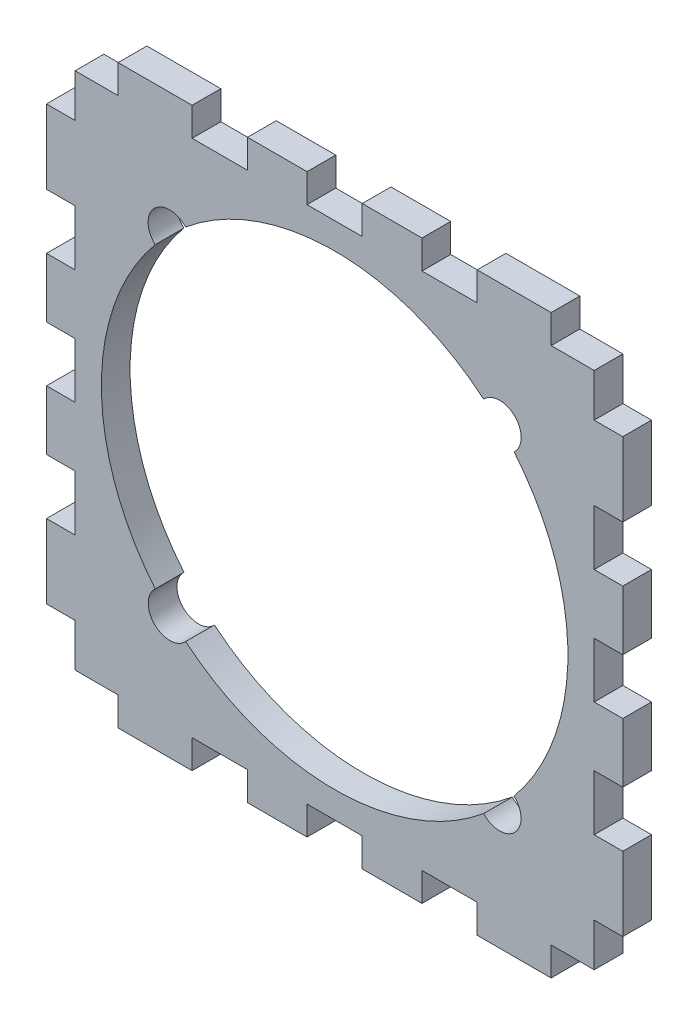
SolidWorks part; units mm, degrees
ref_plane "Front Plane" through (0, 0, 0) normal (0, 0, 1) x (1, 0, 0)
ref_plane "Top Plane" through (0, 0, 0) normal (0, 1, 0) x (1, 0, 0)
ref_plane "Right Plane" through (0, 0, 0) normal (1, 0, 0) x (0, 0, -1)
sketch "Model" plane through (0, 0, 0) normal (0, 0, 1) x (1, 0, 0)
  line L0 (-5.9972, 216.8283) -> (0, 216.8283)
  line L1 (0, 216.8283) -> (0, 220.8147)
  line L2 (0, 220.8147) -> (10.3011, 220.8147)
  line L3 (10.3011, 220.8147) -> (10.3011, 216.8283)
  line L4 (10.3011, 216.8283) -> (18.0269, 216.8283)
  line L5 (18.0269, 216.8283) -> (18.0269, 220.8147)
  line L6 (18.0269, 220.8147) -> (26.3172, 220.8147)
  line L7 (26.3172, 220.8147) -> (26.3172, 216.8283)
  line L8 (26.3172, 216.8283) -> (34.0078, 216.8283)
  line L9 (34.0078, 216.8283) -> (34.0078, 220.8147)
  line L10 (34.0078, 220.8147) -> (42.3333, 220.8147)
  line L11 (42.3333, 220.8147) -> (42.3333, 216.8283)
  line L12 (42.3333, 216.8283) -> (50.0239, 216.8283)
  line L13 (50.0239, 216.8283) -> (50.0239, 220.8147)
  line L14 (50.0239, 220.8147) -> (60.325, 220.8147)
  line L15 (60.325, 220.8147) -> (60.325, 216.8283)
  line L16 (60.325, 216.8283) -> (66.3222, 216.8283)
  line L17 (66.3222, 216.8283) -> (66.3222, 210.8311)
  line L18 (66.3222, 210.8311) -> (70.3086, 210.8311)
  line L19 (70.3086, 210.8311) -> (70.3086, 200.53)
  line L20 (70.3086, 200.53) -> (66.3222, 200.53)
  line L21 (66.3222, 200.53) -> (66.3222, 192.8042)
  line L22 (66.3222, 192.8042) -> (70.3086, 192.8042)
  line L23 (70.3086, 192.8042) -> (70.3086, 184.5139)
  line L24 (70.3086, 184.5139) -> (66.3222, 184.5139)
  line L25 (66.3222, 184.5139) -> (66.3222, 176.8233)
  line L26 (66.3222, 176.8233) -> (70.3086, 176.8233)
  line L27 (70.3086, 176.8233) -> (70.3086, 168.533)
  line L28 (70.3086, 168.533) -> (66.3222, 168.533)
  line L29 (66.3222, 168.533) -> (66.3222, 160.8072)
  line L30 (66.3222, 160.8072) -> (70.3086, 160.8072)
  line L31 (70.3086, 160.8072) -> (70.3086, 150.5061)
  line L32 (70.3086, 150.5061) -> (66.3222, 150.5061)
  line L33 (66.3222, 150.5061) -> (66.3222, 144.5089)
  line L34 (66.3222, 144.5089) -> (60.325, 144.5089)
  line L35 (60.325, 144.5089) -> (60.325, 140.5225)
  line L36 (60.325, 140.5225) -> (50.0239, 140.5225)
  line L37 (50.0239, 140.5225) -> (50.0239, 144.5089)
  line L38 (50.0239, 144.5089) -> (42.3333, 144.5089)
  line L39 (42.3333, 144.5089) -> (42.3333, 140.5225)
  line L40 (42.3333, 140.5225) -> (34.0078, 140.5225)
  line L41 (34.0078, 140.5225) -> (34.0078, 144.5089)
  line L42 (34.0078, 144.5089) -> (26.3172, 144.5089)
  line L43 (26.3172, 144.5089) -> (26.3172, 140.5225)
  line L44 (26.3172, 140.5225) -> (18.0269, 140.5225)
  line L45 (18.0269, 140.5225) -> (18.0269, 144.5089)
  line L46 (18.0269, 144.5089) -> (10.3011, 144.5089)
  line L47 (10.3011, 144.5089) -> (10.3011, 140.5225)
  line L48 (10.3011, 140.5225) -> (0, 140.5225)
  line L49 (0, 140.5225) -> (0, 144.5089)
  line L50 (0, 144.5089) -> (-5.9972, 144.5089)
  line L51 (-5.9972, 144.5089) -> (-5.9972, 150.5061)
  line L52 (-5.9972, 150.5061) -> (-9.9836, 150.5061)
  line L53 (-9.9836, 150.5061) -> (-9.9836, 160.8072)
  line L54 (-9.9836, 160.8072) -> (-5.9972, 160.8072)
  line L55 (-5.9972, 160.8072) -> (-5.9972, 168.533)
  line L56 (-5.9972, 168.533) -> (-9.9836, 168.533)
  line L57 (-9.9836, 168.533) -> (-9.9836, 176.8233)
  line L58 (-9.9836, 176.8233) -> (-5.9972, 176.8233)
  line L59 (-5.9972, 176.8233) -> (-5.9972, 184.5139)
  line L60 (-5.9972, 184.5139) -> (-9.9836, 184.5139)
  line L61 (-9.9836, 184.5139) -> (-9.9836, 192.8042)
  line L62 (-9.9836, 192.8042) -> (-5.9972, 192.8042)
  line L63 (-5.9972, 192.8042) -> (-5.9972, 200.53)
  line L64 (-5.9972, 200.53) -> (-9.9836, 200.53)
  line L65 (-9.9836, 200.53) -> (-9.9836, 210.8311)
  line L66 (-9.9836, 210.8311) -> (-5.9972, 210.8311)
  line L67 (-5.9972, 210.8311) -> (-5.9972, 216.8283)
  line L68 (28.2375, 180.6686) -> (32.0875, 180.6686)
  line L71 (28.2375, 200.5186) -> (32.0875, 200.5186)
  line L72 (28.2375, 200.5186) -> (28.2375, 160.8186)
  line L73 (28.2375, 160.8186) -> (32.0875, 160.8186)
  line L74 (32.0875, 200.5186) -> (32.0875, 160.8186)
  arc A0 (5.1529, 201.4236) -> (5.1678, 159.8956) centre (30.1625, 180.6686) ccw
  arc A1 (55.1721, 201.4236) -> (50.9355, 205.6633) centre (53.1517, 203.6413) ccw
  arc A2 (5.1678, 159.8956) -> (9.4075, 155.659) centre (7.1898, 157.6794) ccw
  arc A3 (55.1572, 159.8956) -> (50.9175, 155.659) centre (53.1352, 157.6794) cw
  arc A4 (5.1529, 201.4236) -> (9.3895, 205.6633) centre (7.1733, 203.6413) cw
  arc A5 (9.4075, 155.659) -> (50.9175, 155.659) centre (30.1625, 180.6686) ccw
  arc A6 (55.1572, 159.8956) -> (55.1721, 201.4236) centre (30.1625, 180.6686) ccw
  arc A7 (50.9355, 205.6633) -> (9.3895, 205.6633) centre (30.1625, 180.6686) ccw
  point P1 (30.1625, 148.1686)
  point P5 (30.1625, 213.1686)
  point P77 (30.1625, 180.6603)
  point P78 (30.1625, 180.6686)
  point P79 (30.1625, 180.6603)
  point P84 (30.1625, 180.6686)
  point P101 (30.1625, 180.6686)
  dimension "D1" = 6
  dimension "D2" = 2
  dimension "D5" = 65
  dimension "D4" = 39.7
  dimension "D6" = 3.85
extrude "Boss-Extrude1" add sketch "Model" along normal blind 4
